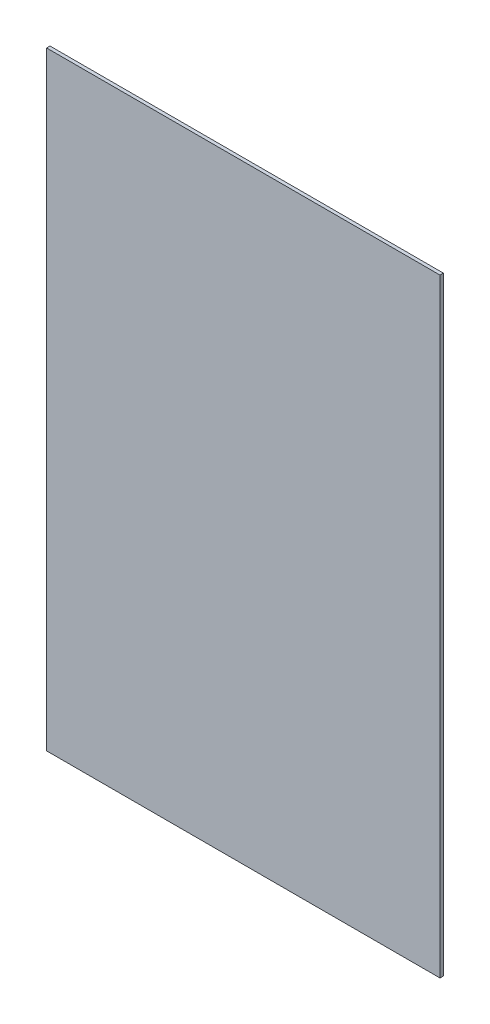
SolidWorks part; units mm, degrees
ref_plane "Plan de face" through (0, 0, 0) normal (0, 0, 1) x (1, 0, 0)
ref_plane "Plan de dessus" through (0, 0, 0) normal (0, 1, 0) x (1, 0, 0)
ref_plane "Plan de droite" through (0, 0, 0) normal (1, 0, 0) x (0, 0, -1)
sketch "Esquisse1" plane through (0, 0, 0) normal (0, 0, 1) x (1, 0, 0)
  line L1 (-184.15, 285) -> (184.15, 285)
  line L2 (-184.15, 285) -> (-184.15, -285)
  line L3 (-184.15, -285) -> (184.15, -285)
  line L4 (184.15, 285) -> (184.15, -285)
  point P4 (0, -285)
  point P6 (184.15, 0)
  dimension "D1" = 368.3
  dimension "D2" = 570
extrude "Boss.-Extru.1" add sketch "Esquisse1" along normal blind 3.175
